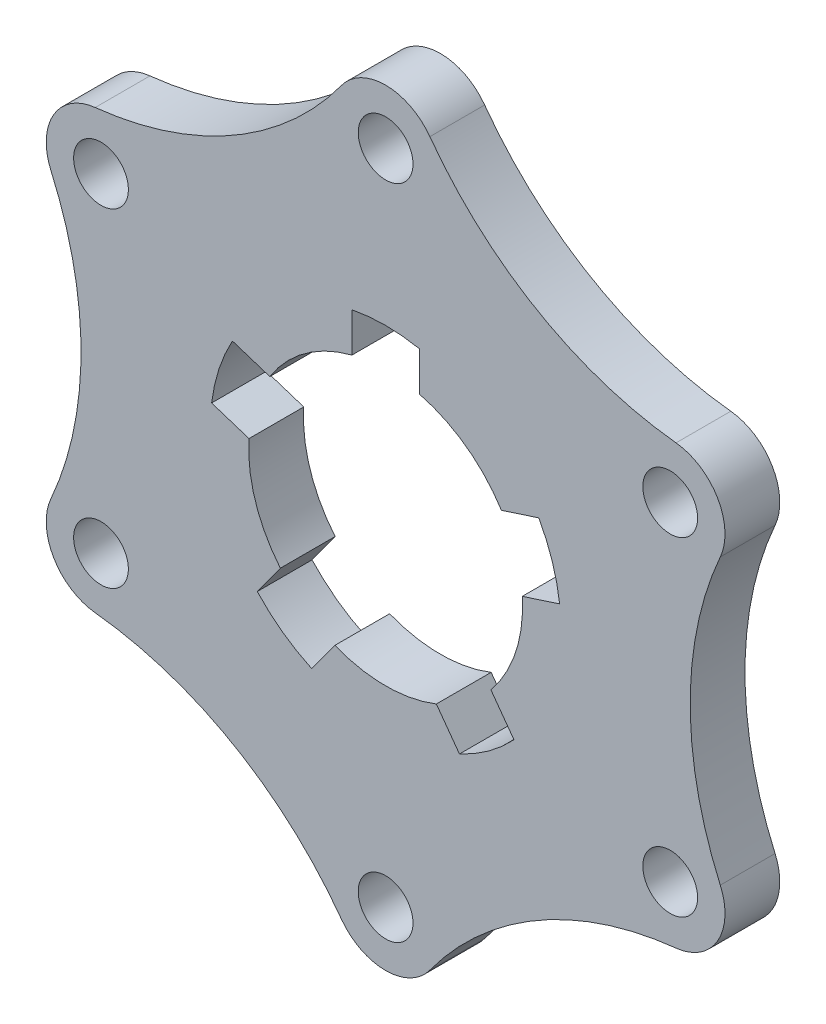
SolidWorks part; units mm, degrees
ref_plane "Alzado" through (0, 0, 0) normal (0, 0, 1) x (1, 0, 0)
ref_plane "Planta" through (0, 0, 0) normal (0, 1, 0) x (1, 0, 0)
ref_plane "Vista lateral" through (0, 0, 0) normal (1, 0, 0) x (0, 0, -1)
sketch "Croquis1" plane through (0, 0, 0) normal (0, 0, 1) x (1, 0, 0)
  circle A0 centre (0, 0) radius 60 construction
  arc A1 (8.0816, 65.8896) -> (-8.0816, 65.8896) centre (0, 60) ccw
  arc A2 (61.1029, 25.9459) -> (53.0213, 39.9437) centre (51.9615, 30) ccw
  arc A3 (53.0213, -39.9437) -> (61.1029, -25.9459) centre (51.9615, -30) ccw
  arc A4 (-8.0816, -65.8896) -> (8.0816, -65.8896) centre (0, -60) ccw
  arc A5 (-61.1029, -25.9459) -> (-53.0213, -39.9437) centre (-51.9615, -30) ccw
  arc A6 (-53.0213, 39.9437) -> (-61.1029, 25.9459) centre (-51.9615, 30) ccw
  arc A7 (-53.0213, 39.9437) -> (-8.0816, 65.8896) centre (-59.8038, 103.5833) ccw
  arc A8 (8.0816, 65.8896) -> (53.0213, 39.9437) centre (59.8038, 103.5833) ccw
  arc A9 (61.1029, 25.9459) -> (61.1029, -25.9459) centre (119.6077, 0) ccw
  arc A10 (53.0213, -39.9437) -> (8.0816, -65.8896) centre (59.8038, -103.5833) ccw
  arc A11 (-8.0816, -65.8896) -> (-53.0213, -39.9437) centre (-59.8038, -103.5833) ccw
  arc A12 (-61.1029, -25.9459) -> (-61.1029, 25.9459) centre (-119.6077, 0) ccw
  point P18 (0, 0)
  point P37 (0, 0)
  dimension "D1" = 120
  dimension "D2" = 20
  dimension "D4" = 64
  dimension "D3" = 6
  dimension "D5" = 6
extrude "Saliente-Extruir1" add sketch "Croquis1" against normal blind 10
sketch "Croquis2" plane through (0, 0, 0) normal (0, 0, 1) x (1, 0, 0)
  line L0 (24.9462, 1.639) -> (31.7669, 3.8552)
  line L2 (-6.15, 24.2317) -> (-6.15, 31.4035)
  line L4 (6.15, 24.2317) -> (6.15, 31.4035)
  line L5 (21.1453, 13.337) -> (27.966, 15.5532)
  line L6 (9.2676, -23.2188) -> (13.483, -29.0208)
  line L7 (19.2185, -15.989) -> (23.4339, -21.7911)
  line L8 (-19.2185, -15.989) -> (-23.4339, -21.7911)
  line L9 (-9.2676, -23.2188) -> (-13.483, -29.0208)
  line L10 (-21.1453, 13.337) -> (-27.966, 15.5532)
  line L11 (-24.9462, 1.639) -> (-31.7669, 3.8552)
  circle A0 centre (0, 60) radius 5
  circle A1 centre (51.9615, 30) radius 5
  circle A2 centre (51.9615, -30) radius 5
  circle A3 centre (0, -60) radius 5
  circle A4 centre (-51.9615, -30) radius 5
  circle A5 centre (-51.9615, 30) radius 5
  circle A6 centre (0, 0) radius 60 construction
  arc A7 (-6.15, 24.2317) -> (-21.1453, 13.337) centre (0, 0) ccw
  arc A8 (6.15, 31.4035) -> (-6.15, 31.4035) centre (0, 0) ccw
  arc A9 (31.7669, 3.8552) -> (27.966, 15.5532) centre (0, 0) ccw
  arc A10 (13.483, -29.0208) -> (23.4339, -21.7911) centre (0, 0) ccw
  arc A11 (-23.4339, -21.7911) -> (-13.483, -29.0208) centre (0, 0) ccw
  arc A12 (-53.0213, 39.9437) -> (-8.0816, 65.8896) centre (-59.8038, 103.5833) ccw
  arc A13 (-53.0213, 39.9437) -> (-61.1029, 25.9459) centre (-51.9615, 30) ccw
  arc A14 (-61.1029, -25.9459) -> (-61.1029, 25.9459) centre (-119.6077, 0) ccw
  arc A15 (-61.1029, -25.9459) -> (-53.0213, -39.9437) centre (-51.9615, -30) ccw
  arc A16 (-8.0816, -65.8896) -> (-53.0213, -39.9437) centre (-59.8038, -103.5833) ccw
  arc A17 (-8.0816, -65.8896) -> (8.0816, -65.8896) centre (0, -60) ccw
  arc A18 (53.0213, -39.9437) -> (8.0816, -65.8896) centre (59.8038, -103.5833) ccw
  arc A19 (53.0213, -39.9437) -> (61.1029, -25.9459) centre (51.9615, -30) ccw
  arc A20 (61.1029, 25.9459) -> (61.1029, -25.9459) centre (119.6077, 0) ccw
  arc A21 (61.1029, 25.9459) -> (53.0213, 39.9437) centre (51.9615, 30) ccw
  arc A22 (8.0816, 65.8896) -> (53.0213, 39.9437) centre (59.8038, 103.5833) ccw
  arc A23 (8.0816, 65.8896) -> (-8.0816, 65.8896) centre (0, 60) ccw
  arc A24 (-53.0213, 39.9437) -> (-8.0816, 65.8896) centre (-59.8038, 103.5833) ccw
  arc A25 (-53.0213, 39.9437) -> (-61.1029, 25.9459) centre (-51.9615, 30) ccw
  arc A26 (-61.1029, -25.9459) -> (-61.1029, 25.9459) centre (-119.6077, 0) ccw
  arc A27 (-61.1029, -25.9459) -> (-53.0213, -39.9437) centre (-51.9615, -30) ccw
  arc A28 (-8.0816, -65.8896) -> (-53.0213, -39.9437) centre (-59.8038, -103.5833) ccw
  arc A29 (-8.0816, -65.8896) -> (8.0816, -65.8896) centre (0, -60) ccw
  arc A30 (53.0213, -39.9437) -> (8.0816, -65.8896) centre (59.8038, -103.5833) ccw
  arc A31 (53.0213, -39.9437) -> (61.1029, -25.9459) centre (51.9615, -30) ccw
  arc A32 (61.1029, 25.9459) -> (61.1029, -25.9459) centre (119.6077, 0) ccw
  arc A33 (61.1029, 25.9459) -> (53.0213, 39.9437) centre (51.9615, 30) ccw
  arc A34 (8.0816, 65.8896) -> (53.0213, 39.9437) centre (59.8038, 103.5833) ccw
  arc A35 (8.0816, 65.8896) -> (-8.0816, 65.8896) centre (0, 60) ccw
  arc A36 (-27.966, 15.5532) -> (-31.7669, 3.8552) centre (0, 0) ccw
  arc A37 (-24.9462, 1.639) -> (-19.2185, -15.989) centre (0, 0) ccw
  arc A38 (21.1453, 13.337) -> (6.15, 24.2317) centre (0, 0) ccw
  arc A39 (19.2185, -15.989) -> (24.9462, 1.639) centre (0, 0) ccw
  arc A40 (-9.2676, -23.2188) -> (9.2676, -23.2188) centre (0, 0) ccw
  point P3 (0, 32)
  point P8 (0, 0)
  point P39 (0, 0)
  point P48 (27.966, 15.5532)
  point P49 (0, 0)
  point P64 (0, 0)
  dimension "D2" = 10
  dimension "D4" = 50
  dimension "D5" = 64
  dimension "D6" = 12.3
  dimension "D1" = 0
  dimension "D3" = 6
  dimension "D7" = 5
extrude "Cortar-Extruir3" cut sketch "Croquis2" against normal through all contours A5 | A0 | A1 | A2 | A3 | A4 | L2 A8 L4 A38 L5 A9 L0 A39 L7 A10 L6 A40 L9 A11 L8 A37 L11 A36 L10 A7
